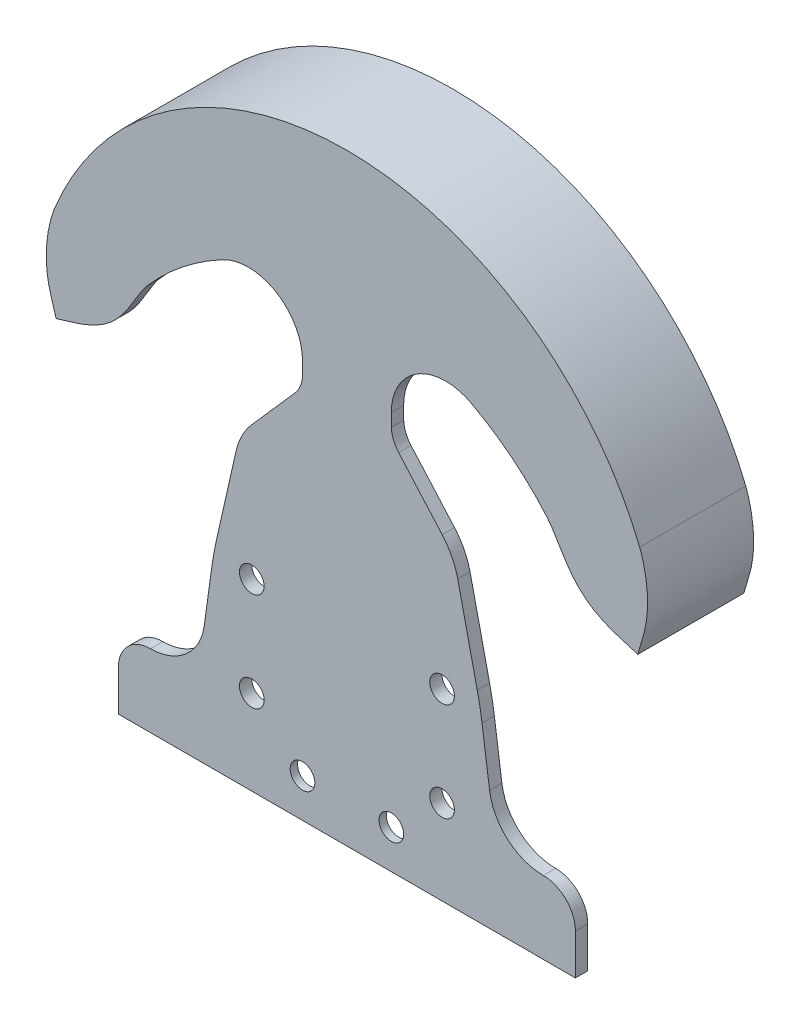
SolidWorks part; units mm, degrees
ref_plane "前视基准面" through (0, 0, 0) normal (0, 0, 1) x (1, 0, 0)
ref_plane "上视基准面" through (0, 0, 0) normal (0, 1, 0) x (1, 0, 0)
ref_plane "右视基准面" through (0, 0, 0) normal (1, 0, 0) x (0, 0, -1)
sketch "草图1" plane through (0, 0, 0) normal (0, 0, 1) x (1, 0, 0)
  line L50 (-253.4507, 153.8906) -> (-233.4507, 153.8906) construction
  line L51 (-253.4507, 153.8906) -> (-253.4507, 178.8906) construction
  line L52 (-233.4507, 153.8906) -> (-233.4507, 178.8906) construction
  line L56 (-261.4507, 145.8906) -> (-225.4507, 145.8906)
  line L57 (-225.4507, 145.8906) -> (-225.4507, 178.8906)
  line L58 (-261.4507, 145.8906) -> (-261.4507, 178.8906)
  arc A46 (-156.2727, 178.8906) -> (-189.3331, 205.3612) centre (-243.4507, 103.8906) ccw construction
  arc A47 (-297.5684, 205.3612) -> (-330.6287, 178.8906) centre (-243.4507, 103.8906) ccw construction
  arc A48 (-233.4507, 178.8906) -> (-189.3331, 205.3612) centre (-203.4507, 178.8906) cw construction
  arc A49 (-253.4507, 178.8906) -> (-297.5684, 205.3612) centre (-283.4507, 178.8906) ccw construction
  arc A50 (-354.6937, 178.8906) -> (-132.2077, 178.8906) centre (-243.4507, 133.8906) cw construction
  arc A56 (-225.4507, 178.8906) -> (-193.0978, 198.3024) centre (-203.4507, 178.8906) cw
  arc A57 (-162.3373, 173.6732) -> (-193.0978, 198.3024) centre (-243.4507, 103.8906) ccw
  arc A58 (-362.1099, 181.8906) -> (-124.7915, 181.8906) centre (-243.4507, 133.8906) cw
  arc A59 (-293.8037, 198.3024) -> (-324.5641, 173.6732) centre (-243.4507, 103.8906) ccw
  arc A60 (-261.4507, 178.8906) -> (-293.8037, 198.3024) centre (-283.4507, 178.8906) ccw
  spline S0 degree 3 poles (-330.6287, 178.8906) (-333.7557, 175.2558) (-339.6986, 163.334) (-346.9011, 156.6664) (-355.9507, 153.8906) knots 0 0 0 0 0.445001 1 1 1 1 construction
  spline S1 degree 3 poles (-156.2727, 178.8906) (-153.1457, 175.2558) (-147.2029, 163.334) (-140.0004, 156.6664) (-130.9507, 153.8906) knots 0 0 0 0 0.445001 1 1 1 1 construction
  spline S2 degree 3 poles (-354.6937, 178.8906) (-355.9795, 175.712) (-359.1189, 164.6336) (-355.9507, 153.8906) knots 0 0 0 0 1 1 1 1 construction
  spline S3 degree 3 poles (-132.2077, 178.8906) (-130.922, 175.712) (-127.7826, 164.6336) (-130.9507, 153.8906) knots 0 0 0 0 1 1 1 1 construction
  spline S12 degree 1 poles (-162.3373, 173.6732) (-125.565, 143.8707) knots 0 0 1 1 construction
  spline S13 degree 1 poles (-124.7915, 181.8906) (-125.565, 143.8707) knots 0 0 1 1 construction
  spline S14 degree 1 poles (-362.1099, 181.8906) (-361.3364, 143.8707) knots 0 0 1 1 construction
  spline S15 degree 1 poles (-324.5641, 173.6732) (-361.3364, 143.8707) knots 0 0 1 1 construction
  spline S16 degree 3 poles (-162.3373, 173.6732) (-162.1569, 173.4635) (-161.8222, 173.0548) (-161.0635, 172.0508) (-160.064, 170.5851) (-158.7871, 168.5438) (-156.9976, 165.5682) (-154.5713, 161.5499) (-151.6264, 157.5381) (-148.6726, 154.4947) (-146.127, 152.3645) (-143.2514, 150.4432) (-140.0504, 148.7514) (-137.1153, 147.5257) (-134.8798, 146.744) (-133.8248, 146.4053) (-133.3042, 146.2445) (-133.0182, 146.1569) (-132.4962, 145.9967) (-131.7617, 145.7715) (-130.5803, 145.4091) (-128.5158, 144.7759) (-126.7452, 144.2327) (-125.565, 143.8707) knots 0 0 0 0 0.036189 0.072379 0.144757 0.217136 0.289514 0.434271 0.579028 0.651407 0.723786 0.796164 0.868543 0.940921 0.97711 0.995205 0.999729 1.004252 1.0133 1.031394 1.049489 1.085678 1.158057 1.158057 1.158057 1.158057
  spline S17 degree 3 poles (-125.565, 143.8707) (-125.3193, 144.7038) (-124.9508, 145.9533) (-124.4595, 147.6195) (-124.091, 148.8688) (-123.7838, 149.9107) (-123.5384, 150.7425) (-123.3843, 151.2663) (-123.2626, 151.6764) (-123.1032, 152.2295) (-122.8609, 153.1288) (-122.4242, 154.9658) (-121.9752, 157.5299) (-121.6653, 160.535) (-121.5541, 163.4329) (-121.627, 167.132) (-122.0572, 171.3984) (-122.7563, 175.0715) (-123.3797, 177.5891) (-123.8587, 179.2553) (-124.2512, 180.4506) (-124.5608, 181.3048) (-124.7117, 181.6931) (-124.7915, 181.8906) knots 0 0 0 0 0.077543 0.116314 0.155085 0.193857 0.213242 0.232628 0.242321 0.252014 0.271399 0.310171 0.387713 0.465256 0.542799 0.620341 0.775427 0.930512 1.008055 1.085598 1.16314 1.201912 1.240683 1.240683 1.240683 1.240683
  spline S18 degree 3 poles (-362.1099, 181.8906) (-362.1898, 181.6931) (-362.3407, 181.3048) (-362.6502, 180.4506) (-363.0427, 179.2553) (-363.5217, 177.5891) (-364.1452, 175.0715) (-364.8442, 171.3984) (-365.2745, 167.132) (-365.3473, 163.4329) (-365.2362, 160.535) (-364.9262, 157.5299) (-364.4773, 154.9658) (-364.0406, 153.1288) (-363.7982, 152.2295) (-363.6389, 151.6764) (-363.5171, 151.2663) (-363.3631, 150.7425) (-363.1176, 149.9107) (-362.8104, 148.8688) (-362.442, 147.6195) (-361.9506, 145.9533) (-361.5821, 144.7038) (-361.3364, 143.8707) knots 0 0 0 0 0.038771 0.077543 0.155085 0.232628 0.310171 0.465256 0.620341 0.697884 0.775427 0.852969 0.930512 0.969283 0.988669 0.998362 1.008055 1.02744 1.046826 1.085598 1.124369 1.16314 1.240683 1.240683 1.240683 1.240683
  spline S19 degree 3 poles (-361.3364, 143.8707) (-360.1563, 144.2327) (-358.3856, 144.7759) (-356.3211, 145.4091) (-355.1397, 145.7715) (-354.4052, 145.9967) (-353.8832, 146.1569) (-353.5972, 146.2445) (-353.0767, 146.4053) (-352.0217, 146.744) (-349.7862, 147.5257) (-346.851, 148.7514) (-343.65, 150.4432) (-340.7744, 152.3645) (-338.2288, 154.4947) (-335.2751, 157.5381) (-332.3302, 161.5499) (-329.9038, 165.5682) (-328.1143, 168.5438) (-326.8375, 170.5851) (-325.838, 172.0508) (-325.0792, 173.0548) (-324.7446, 173.4635) (-324.5641, 173.6732) knots 0 0 0 0 0.072379 0.108568 0.126662 0.144757 0.153804 0.158328 0.162852 0.180946 0.217136 0.289514 0.361893 0.434271 0.50665 0.579028 0.723786 0.868543 0.940921 1.0133 1.085678 1.121868 1.158057 1.158057 1.158057 1.158057
  dimension "D2" = 8
extrude "凸台-拉伸6" add sketch "草图1" along normal blind 5
sketch "草图4" plane through (0, 0, 0) normal (0, 0, -1) x (-1, 0, 0)
  line L3 (261.4507, 145.8906) -> (261.4507, 178.8906)
  line L4 (225.4507, 178.8906) -> (225.4507, 145.8906)
  line L5 (225.4507, 145.8906) -> (261.4507, 145.8906)
  line L9 (125.565, 143.8707) -> (162.3373, 173.6732) construction
  line L10 (127.1703, 149.0333) -> (160.2404, 175.8353) construction
  line L11 (127.1703, 149.0333) -> (125.565, 143.8707)
  line L12 (359.7312, 149.0333) -> (361.3364, 143.8707)
  line L13 (324.5641, 173.6732) -> (361.3364, 143.8707) construction
  line L14 (225.4507, 178.8906) -> (225.4507, 145.8906) construction
  line L15 (228.4507, 178.8906) -> (228.4507, 148.8906) construction
  line L16 (225.4507, 145.8906) -> (261.4507, 145.8906) construction
  line L17 (228.4507, 148.8906) -> (258.4507, 148.8906) construction
  line L18 (261.4507, 145.8906) -> (261.4507, 178.8906) construction
  line L19 (258.4507, 148.8906) -> (258.4507, 178.8906) construction
  line L20 (326.6611, 175.8353) -> (359.7312, 149.0333) construction
  arc A2 (359.3288, 180.7656) -> (127.5726, 180.7656) centre (243.4507, 133.8906) ccw
  arc A5 (293.8037, 198.3024) -> (261.4507, 178.8906) centre (283.4507, 178.8906) ccw
  arc A6 (324.5641, 173.6732) -> (293.8037, 198.3024) centre (243.4507, 103.8906) ccw
  arc A7 (362.1099, 181.8906) -> (124.7915, 181.8906) centre (243.4507, 133.8906) ccw
  arc A8 (193.0978, 198.3024) -> (162.3373, 173.6732) centre (243.4507, 103.8906) ccw
  arc A9 (225.4507, 178.8906) -> (193.0978, 198.3024) centre (203.4507, 178.8906) ccw
  arc A12 (362.1099, 181.8906) -> (124.7915, 181.8906) centre (243.4507, 133.8906) ccw
  arc A15 (193.0978, 198.3024) -> (162.3373, 173.6732) centre (243.4507, 103.8906) ccw construction
  arc A16 (191.686, 200.9494) -> (160.2404, 175.8353) centre (243.4507, 103.8906) ccw construction
  arc A17 (228.4507, 178.8906) -> (191.686, 200.9494) centre (203.4507, 178.8906) ccw construction
  arc A18 (225.4507, 178.8906) -> (193.0978, 198.3024) centre (203.4507, 178.8906) ccw construction
  arc A19 (295.2154, 200.9494) -> (258.4507, 178.8906) centre (283.4507, 178.8906) ccw construction
  arc A20 (293.8037, 198.3024) -> (261.4507, 178.8906) centre (283.4507, 178.8906) ccw construction
  arc A21 (326.6611, 175.8353) -> (295.2154, 200.9494) centre (243.4507, 103.8906) ccw construction
  arc A22 (324.5641, 173.6732) -> (293.8037, 198.3024) centre (243.4507, 103.8906) ccw construction
  spline S1 degree 1 poles (359.7312, 149.0333) (359.3288, 180.7656) knots 0 0 1 1 construction
  spline S2 degree 1 poles (127.5726, 180.7656) (127.1703, 149.0333) knots 0 0 1 1 construction
  spline S4 degree 3 poles (-334.5281, 925.7249) (324.5328, 165.4388) (319.5248, 180.4044) (325.838, 172.0508) (326.8375, 170.5851) (328.1143, 168.5438) (329.9038, 165.5682) (332.3302, 161.5499) (335.2751, 157.5381) (338.2288, 154.4947) (340.7744, 152.3645) (343.65, 150.4432) (346.851, 148.7514) (349.7862, 147.5257) (352.0217, 146.744) (353.0767, 146.4053) (353.5972, 146.2445) (353.8832, 146.1569) (354.4052, 145.9967) (355.1397, 145.7715) (356.3211, 145.4091) (508.7612, 98.6521) (668.3407, 49.562) (-586.821, 461.6535) knots -1.059691 -1.059691 -1.059691 -1.059691 0.036189 0.072379 0.144757 0.217136 0.289514 0.434271 0.579028 0.651407 0.723786 0.796164 0.868543 0.940921 0.97711 0.995205 0.999729 1.004252 1.0133 1.031394 1.049489 1.085678 10.383805 10.383805 10.383805 10.383805 only from (324.5641, 173.6732) to (361.3364, 143.8707)
  spline S5 degree 3 poles (-250.6044, -2792.3967) (190.8544, -432.5756) (276.2458, -144.6702) (362.442, 147.6195) (362.8104, 148.8688) (363.1176, 149.9107) (363.3631, 150.7425) (363.5171, 151.2663) (363.6389, 151.6764) (363.7982, 152.2295) (364.0406, 153.1288) (364.4773, 154.9658) (364.9262, 157.5299) (365.2362, 160.535) (365.3473, 163.4329) (365.2745, 167.132) (364.8442, 171.3984) (364.1452, 175.0715) (363.5217, 177.5891) (363.0427, 179.2553) (362.6502, 180.4506) (357.7609, 193.9423) (356.6698, 170.7419) (-818.7559, 2939.1071) knots -27.051344 -27.051344 -27.051344 -27.051344 0.077543 0.116314 0.155085 0.193857 0.213242 0.232628 0.242321 0.252014 0.271399 0.310171 0.387713 0.465256 0.542799 0.620341 0.775427 0.930512 1.008055 1.085598 1.16314 1.201912 3.535098 3.535098 3.535098 3.535098 only from (361.3364, 143.8707) to (362.1099, 181.8906)
  spline S6 degree 3 poles (1305.6549, 2939.1014) (130.2317, 170.742) (129.1405, 193.9423) (124.2512, 180.4506) (123.8587, 179.2553) (123.3797, 177.5891) (122.7563, 175.0715) (122.0572, 171.3984) (121.627, 167.132) (121.5541, 163.4329) (121.6653, 160.535) (121.9752, 157.5299) (122.4242, 154.9658) (122.8609, 153.1288) (123.1032, 152.2295) (123.2626, 151.6764) (123.3843, 151.2663) (123.5384, 150.7425) (123.7838, 149.9107) (124.091, 148.8688) (124.4595, 147.6195) (210.6549, -144.6678) (296.0456, -432.5708) (737.4948, -2792.3377) knots -2.294413 -2.294413 -2.294413 -2.294413 0.038771 0.077543 0.155085 0.232628 0.310171 0.465256 0.620341 0.697884 0.775427 0.852969 0.930512 0.969283 0.988669 0.998362 1.008055 1.02744 1.046826 1.085598 1.124369 1.16314 28.291801 28.291801 28.291801 28.291801 only from (124.7915, 181.8906) to (125.565, 143.8707)
  spline S7 degree 3 poles (1073.7269, 461.6549) (-181.4396, 49.5619) (-21.8599, 98.652) (130.5803, 145.4091) (131.7617, 145.7715) (132.4962, 145.9967) (133.0182, 146.1569) (133.3042, 146.2445) (133.8248, 146.4053) (134.8798, 146.744) (137.1153, 147.5257) (140.0504, 148.7514) (143.2514, 150.4432) (146.127, 152.3645) (148.6726, 154.4947) (151.6264, 157.5381) (154.5713, 161.5499) (156.9976, 165.5682) (158.7871, 168.5438) (160.064, 170.5851) (161.0635, 172.0508) (167.3762, 180.4039) (162.3693, 165.4409) (821.2885, 925.5622) knots -9.225759 -9.225759 -9.225759 -9.225759 0.072379 0.108568 0.126662 0.144757 0.153804 0.158328 0.162852 0.180946 0.217136 0.289514 0.361893 0.434271 0.50665 0.579028 0.723786 0.868543 0.940921 1.0133 1.085678 1.121868 2.21767 2.21767 2.21767 2.21767 only from (125.565, 143.8707) to (162.3373, 173.6732)
  spline S9 degree 3 poles (361.3364, 143.8707) (361.5821, 144.7038) (361.9506, 145.9533) (362.442, 147.6195) (362.8104, 148.8688) (363.1176, 149.9107) (363.3631, 150.7425) (363.5171, 151.2663) (363.6389, 151.6764) (363.7982, 152.2295) (364.0406, 153.1288) (364.4773, 154.9658) (364.9262, 157.5299) (365.2362, 160.535) (365.3473, 163.4329) (365.2745, 167.132) (364.8442, 171.3984) (364.1452, 175.0715) (363.5217, 177.5891) (363.0427, 179.2553) (362.6502, 180.4506) (362.3407, 181.3048) (362.1898, 181.6931) (362.1099, 181.8906) knots 0 0 0 0 0.077543 0.116314 0.155085 0.193857 0.213242 0.232628 0.242321 0.252014 0.271399 0.310171 0.387713 0.465256 0.542799 0.620341 0.775427 0.930512 1.008055 1.085598 1.16314 1.201912 1.240683 1.240683 1.240683 1.240683
  spline S10 degree 3 poles (124.7915, 181.8906) (124.7117, 181.6931) (124.5608, 181.3048) (124.2512, 180.4506) (123.8587, 179.2553) (123.3797, 177.5891) (122.7563, 175.0715) (122.0572, 171.3984) (121.627, 167.132) (121.5541, 163.4329) (121.6653, 160.535) (121.9752, 157.5299) (122.4242, 154.9658) (122.8609, 153.1288) (123.1032, 152.2295) (123.2626, 151.6764) (123.3843, 151.2663) (123.5384, 150.7425) (123.7838, 149.9107) (124.091, 148.8688) (124.4595, 147.6195) (124.9508, 145.9533) (125.3193, 144.7038) (125.565, 143.8707) knots 0 0 0 0 0.038771 0.077543 0.155085 0.232628 0.310171 0.465256 0.620341 0.697884 0.775427 0.852969 0.930512 0.969283 0.988669 0.998362 1.008055 1.02744 1.046826 1.085598 1.124369 1.16314 1.240683 1.240683 1.240683 1.240683
  spline S13 degree 3 poles (359.7312, 149.0333) (359.9503, 149.7764) (360.224, 150.703) (360.5533, 151.822) (360.6885, 152.2782) (360.8038, 152.6713) (360.9349, 153.1325) (361.1289, 153.859) (361.3909, 154.9529) (361.7356, 156.6602) (362.0512, 158.7728) (362.2681, 161.2567) (362.3663, 164.4692) (362.1847, 168.2714) (361.6304, 172.3741) (361.0068, 175.3191) (360.4768, 177.3386) (360.0784, 178.6753) (359.7576, 179.6311) (359.5087, 180.3104) (359.3912, 180.6114) (359.3288, 180.7656) knots 0.133855 0.133855 0.133855 0.133855 0.203031 0.220326 0.23762 0.246267 0.254914 0.272208 0.306797 0.341385 0.410562 0.479739 0.548915 0.687269 0.825622 0.963976 1.033153 1.102329 1.171506 1.206094 1.240683 1.240683 1.240683 1.240683
  spline S14 degree 3 poles (127.5726, 180.7656) (127.5102, 180.6114) (127.3927, 180.3104) (127.1438, 179.6311) (126.8231, 178.6753) (126.4247, 177.3386) (125.8946, 175.3191) (125.2711, 172.3741) (124.7168, 168.2714) (124.5352, 164.4692) (124.6334, 161.2567) (124.8502, 158.7728) (125.1658, 156.6602) (125.5105, 154.9529) (125.7726, 153.859) (125.9665, 153.1325) (126.0976, 152.6713) (126.2129, 152.2782) (126.3481, 151.822) (126.6775, 150.703) (126.9511, 149.7764) (127.1703, 149.0333) knots 0 0 0 0 0.034588 0.069177 0.138354 0.20753 0.276707 0.415061 0.553414 0.691768 0.760944 0.830121 0.899298 0.933886 0.968475 0.985769 0.994416 1.003063 1.020357 1.037651 1.106828 1.106828 1.106828 1.106828
  dimension "D1" = 0
  dimension "D2" = 3
extrude "凸台-拉伸7" add sketch "草图4" along normal blind 35
sketch "草图5" plane through (0, 0, -35) normal (0, 0, -1) x (-1, 0, 0)
  line L0 (243.4507, 145.8906) -> (243.4507, 269.2971) construction
  line L2 (125.565, 143.8707) -> (127.1703, 149.0333)
  line L3 (359.7312, 149.0333) -> (361.3364, 143.8707)
  line L5 (124.7915, 181.8906) -> (125.565, 143.8707) construction
  line L6 (154.9193, 175.9166) -> (155.5588, 144.4809) construction
  line L7 (361.3364, 143.8707) -> (362.1099, 181.8906) construction
  line L8 (331.3427, 144.4809) -> (331.9822, 175.9166) construction
  arc A0 (331.9822, 175.9166) -> (154.9193, 175.9166) centre (243.4507, 133.8906) ccw
  arc A2 (362.1099, 181.8906) -> (124.7915, 181.8906) centre (243.4507, 133.8906) ccw
  arc A3 (359.3288, 180.7656) -> (127.5726, 180.7656) centre (243.4507, 133.8906) ccw
  arc A4 (362.1099, 181.8906) -> (124.7915, 181.8906) centre (243.4507, 133.8906) ccw
  spline S1 degree 3 poles (361.3364, 143.8707) (346.8534, 150.3802) (338.6969, 161.7715) (331.9822, 175.9166) knots 0 0 0 0 1 1 1 1
  spline S4 degree 3 poles (-250.604, -2792.3952) (190.8545, -432.5755) (276.2458, -144.6702) (362.442, 147.6195) (362.8104, 148.8688) (363.1176, 149.9107) (363.3631, 150.7425) (363.5171, 151.2663) (363.6389, 151.6764) (363.7982, 152.2295) (364.0406, 153.1288) (364.4773, 154.9658) (364.9262, 157.5299) (365.2362, 160.535) (365.3473, 163.4329) (365.2744, 167.132) (364.8442, 171.3985) (364.1452, 175.0715) (363.5217, 177.5891) (363.0427, 179.2553) (362.6502, 180.4506) (357.7609, 193.9423) (356.67, 170.7415) (-818.7021, 2938.9834) knots -27.063744 -27.063744 -27.063744 -27.063744 0.065136 0.103907 0.142679 0.18145 0.200836 0.220221 0.229914 0.239607 0.258993 0.297764 0.375307 0.452849 0.530392 0.607935 0.76302 0.918105 0.995648 1.073191 1.150733 1.189505 3.522691 3.522691 3.522691 3.522691 only from (361.3364, 143.8707) to (362.1099, 181.8906)
  spline S5 degree 3 poles (1305.6549, 2939.1014) (130.2317, 170.742) (129.1405, 193.9423) (124.2512, 180.4506) (123.8587, 179.2553) (123.3797, 177.5891) (122.7563, 175.0715) (122.0572, 171.3984) (121.627, 167.132) (121.5541, 163.4329) (121.6653, 160.535) (121.9752, 157.5299) (122.4242, 154.9658) (122.8609, 153.1288) (123.1032, 152.2295) (123.2626, 151.6764) (123.3843, 151.2663) (123.5384, 150.7425) (123.7838, 149.9107) (124.091, 148.8688) (124.4595, 147.6195) (210.6549, -144.6678) (296.0456, -432.5708) (737.4948, -2792.3377) knots -2.294413 -2.294413 -2.294413 -2.294413 0.038771 0.077543 0.155085 0.232628 0.310171 0.465256 0.620341 0.697884 0.775427 0.852969 0.930512 0.969283 0.988669 0.998362 1.008055 1.02744 1.046826 1.085598 1.124369 1.16314 28.291801 28.291801 28.291801 28.291801 only from (124.7915, 181.8906) to (125.565, 143.8707)
  spline S6 degree 3 poles (280.6603, -839.1112) (148.6074, 82.2121) (138.2801, 111.2793) (126.3481, 151.822) (126.2129, 152.2782) (126.0976, 152.6713) (125.9665, 153.1325) (125.7726, 153.859) (125.5105, 154.9529) (125.1658, 156.6602) (124.8502, 158.7728) (124.6334, 161.2567) (124.5352, 164.4692) (124.7168, 168.2714) (125.2711, 172.3741) (125.8946, 175.3191) (126.4247, 177.3386) (126.8231, 178.6753) (127.1438, 179.6311) (129.9096, 187.1786) (129.4062, 176.9576) (509.2581, 1104.9895) knots -3.655588 -3.655588 -3.655588 -3.655588 0.069177 0.086471 0.103765 0.112412 0.121059 0.138354 0.172942 0.20753 0.276707 0.345884 0.415061 0.553414 0.691768 0.830121 0.899298 0.968475 1.037651 1.07224 2.505599 2.505599 2.505599 2.505599 only from (127.1703, 149.0333) to (127.5726, 180.7656)
  spline S7 degree 3 poles (-22.3799, 1105.0463) (357.4953, 176.9572) (356.9918, 187.1788) (359.7576, 179.6311) (360.0784, 178.6753) (360.4768, 177.3386) (361.0068, 175.3191) (361.6304, 172.3741) (362.1847, 168.2714) (362.3663, 164.4692) (362.2681, 161.2567) (362.0512, 158.7728) (361.7356, 156.6602) (361.3909, 154.9529) (361.1289, 153.859) (360.9349, 153.1325) (360.8038, 152.6713) (360.6885, 152.2782) (360.5533, 151.822) (348.6213, 111.2793) (338.2941, 82.2121) (206.2413, -839.1099) knots -1.264946 -1.264946 -1.264946 -1.264946 0.168443 0.203031 0.272208 0.341385 0.410562 0.548915 0.687269 0.825622 0.894799 0.963976 1.033153 1.067741 1.102329 1.119624 1.128271 1.136918 1.154212 1.171506 4.896269 4.896269 4.896269 4.896269 only from (359.3288, 180.7656) to (359.7312, 149.0333)
  spline S8 degree 3 poles (361.3364, 143.8707) (361.5821, 144.7038) (361.9506, 145.9533) (362.442, 147.6195) (362.8104, 148.8688) (363.1176, 149.9107) (363.3631, 150.7425) (363.5171, 151.2663) (363.6389, 151.6764) (363.7982, 152.2295) (364.0406, 153.1288) (364.4773, 154.9658) (364.9262, 157.5299) (365.2362, 160.535) (365.3473, 163.4329) (365.2744, 167.132) (364.8442, 171.3985) (364.1452, 175.0715) (363.5217, 177.5891) (363.0427, 179.2553) (362.6502, 180.4506) (362.3407, 181.3048) (362.1898, 181.6931) (362.1099, 181.8906) knots -0.012407 -0.012407 -0.012407 -0.012407 0.065136 0.103907 0.142679 0.18145 0.200836 0.220221 0.229914 0.239607 0.258993 0.297764 0.375307 0.452849 0.530392 0.607935 0.76302 0.918105 0.995648 1.073191 1.150733 1.189505 1.228276 1.228276 1.228276 1.228276
  spline S9 degree 3 poles (124.7915, 181.8906) (124.7117, 181.6931) (124.5608, 181.3048) (124.2512, 180.4506) (123.8587, 179.2553) (123.3797, 177.5891) (122.7563, 175.0715) (122.0572, 171.3984) (121.627, 167.132) (121.5541, 163.4329) (121.6653, 160.535) (121.9752, 157.5299) (122.4242, 154.9658) (122.8609, 153.1288) (123.1032, 152.2295) (123.2626, 151.6764) (123.3843, 151.2663) (123.5384, 150.7425) (123.7838, 149.9107) (124.091, 148.8688) (124.4595, 147.6195) (124.9508, 145.9533) (125.3193, 144.7038) (125.565, 143.8707) knots 0 0 0 0 0.038771 0.077543 0.155085 0.232628 0.310171 0.465256 0.620341 0.697884 0.775427 0.852969 0.930512 0.969283 0.988669 0.998362 1.008055 1.02744 1.046826 1.085598 1.124369 1.16314 1.240683 1.240683 1.240683 1.240683
  spline S10 degree 3 poles (125.565, 143.8707) (140.048, 150.3802) (148.2046, 161.7715) (154.9193, 175.9166) knots 0 0 0 0 1 1 1 1
  dimension "D1" = 0
extrude "凸台-拉伸9" add sketch "草图5" along normal blind 3
sketch "草图7" plane through (0, 0, 5) normal (0, 0, 1) x (1, 0, 0)
  line L3 (-261.4507, 178.8906) -> (-261.4507, 145.8906)
  line L4 (-261.4507, 145.8906) -> (-225.4507, 145.8906)
  line L5 (-225.4507, 145.8906) -> (-225.4507, 178.8906)
  line L8 (-225.4507, 173.6266) -> (-225.4507, 178.8906)
  line L35 (-301.286, 66.1064) -> (-298.218, 88.2296)
  line L36 (-296.2945, 98.8105) -> (-288.3797, 133.9009)
  line L37 (-282.0717, 146.2538) -> (-264.4482, 166.2496)
  line L38 (-261.4507, 174.1841) -> (-261.4507, 178.8906)
  line L41 (-204.8427, 146.2538) -> (-222.4662, 166.2496)
  line L42 (-190.6199, 98.8105) -> (-198.5347, 133.9009)
  line L43 (-185.6284, 66.1064) -> (-188.6964, 88.2296)
  line L54 (-336.0774, 34.1284) -> (-336.0774, 17.6479)
  line L55 (-336.0774, 17.6479) -> (-150.8369, 17.6479)
  line L56 (-150.8369, 34.1284) -> (-150.8369, 17.6479)
  arc A5 (-193.0978, 198.3024) -> (-225.4507, 178.8906) centre (-203.4507, 178.8906) ccw
  arc A6 (-162.3373, 173.6732) -> (-193.0978, 198.3024) centre (-243.4507, 103.8906) ccw
  arc A7 (-124.7915, 181.8906) -> (-362.1099, 181.8906) centre (-243.4507, 133.8906) ccw
  arc A8 (-293.8037, 198.3024) -> (-324.5641, 173.6732) centre (-243.4507, 103.8906) ccw
  arc A9 (-261.4507, 178.8906) -> (-293.8037, 198.3024) centre (-283.4507, 178.8906) ccw
  arc A10 (-193.0978, 198.3024) -> (-225.4507, 178.8906) centre (-203.4507, 178.8906) ccw
  arc A11 (-162.3373, 173.6732) -> (-193.0978, 198.3024) centre (-243.4507, 103.8906) ccw
  arc A12 (-124.7915, 181.8906) -> (-362.1099, 181.8906) centre (-243.4507, 133.8906) ccw
  arc A13 (-293.8037, 198.3024) -> (-324.5641, 173.6732) centre (-243.4507, 103.8906) ccw
  arc A14 (-261.4507, 178.8906) -> (-293.8037, 198.3024) centre (-283.4507, 178.8906) ccw
  arc A36 (-323.0774, 47.1284) -> (-301.286, 66.1064) centre (-323.0774, 69.1284) ccw
  arc A37 (-298.218, 88.2296) -> (-296.2945, 98.8105) centre (-171.4313, 70.6469) cw
  arc A38 (-288.3797, 133.9009) -> (-282.0717, 146.2538) centre (-261.0658, 127.7402) cw
  arc A39 (-264.4482, 166.2496) -> (-261.4507, 174.1841) centre (-273.4507, 174.1841) ccw
  arc A40 (-222.4662, 166.2496) -> (-225.4507, 173.6266) centre (-213.4637, 174.1841) cw
  arc A41 (-204.8427, 146.2538) -> (-198.5347, 133.9009) centre (-225.8485, 127.7402) cw
  arc A42 (-188.6964, 88.2296) -> (-190.6199, 98.8105) centre (-315.4831, 70.6469) ccw
  arc A43 (-163.8369, 47.1284) -> (-185.6284, 66.1064) centre (-163.8369, 69.1284) cw
  arc A45 (-336.0774, 34.1284) -> (-323.0774, 47.1284) centre (-323.0774, 34.1284) cw
  arc A46 (-150.8369, 34.1284) -> (-163.8369, 47.1284) centre (-163.8369, 34.1284) ccw
  spline S4 degree 3 poles (-3430.7462, 3955.4122) (-150.4817, 134.4946) (-171.4156, 185.7488) (-161.0635, 172.0508) (-160.064, 170.5851) (-158.7871, 168.5438) (-156.9976, 165.5682) (-154.5713, 161.5499) (-151.6264, 157.5381) (-148.6726, 154.4947) (-146.127, 152.3645) (-143.2514, 150.4432) (-140.0504, 148.7514) (-137.1153, 147.5257) (-134.8798, 146.744) (-133.8248, 146.4053) (-133.3042, 146.2445) (-133.0182, 146.1569) (-132.4962, 145.9967) (-131.7617, 145.7715) (-130.5803, 145.4091) (108.4504, 72.0927) (365.4909, -7.1004) (-4875.1127, 1705.8776) knots -1.830248 -1.830248 -1.830248 -1.830248 0.036189 0.072379 0.144757 0.217136 0.289514 0.434271 0.579028 0.651407 0.723786 0.796164 0.868543 0.940921 0.97711 0.995205 0.999729 1.004252 1.0133 1.031394 1.049489 1.085678 15.696264 15.696264 15.696264 15.696264 only from (-162.3373, 173.6732) to (-125.565, 143.8707)
  spline S5 degree 3 poles (-1100.1242, -4759.1447) (-334.975, -563.7382) (-230.293, -211.26) (-124.4595, 147.6195) (-124.091, 148.8688) (-123.7838, 149.9107) (-123.5384, 150.7425) (-123.3843, 151.2663) (-123.2626, 151.6764) (-123.1032, 152.2295) (-122.8609, 153.1288) (-122.4242, 154.9658) (-121.9752, 157.5299) (-121.6653, 160.535) (-121.5541, 163.4329) (-121.627, 167.132) (-122.0572, 171.3984) (-122.7563, 175.0715) (-123.3797, 177.5891) (-123.8587, 179.2553) (-124.2512, 180.4506) (-130.0019, 196.3193) (-130.5081, 161.0995) (-2085.8561, 4779.5647) knots -33.249546 -33.249546 -33.249546 -33.249546 0.077543 0.116314 0.155085 0.193857 0.213242 0.232628 0.242321 0.252014 0.271399 0.310171 0.387713 0.465256 0.542799 0.620341 0.775427 0.930512 1.008055 1.085598 1.16314 1.201912 3.966644 3.966644 3.966644 3.966644 only from (-125.565, 143.8707) to (-124.7915, 181.8906)
  spline S6 degree 3 poles (1599.0286, 4779.7392) (-356.3933, 161.0986) (-356.8995, 196.3195) (-362.6502, 180.4506) (-363.0427, 179.2553) (-363.5217, 177.5891) (-364.1452, 175.0715) (-364.8442, 171.3984) (-365.2745, 167.132) (-365.3473, 163.4329) (-365.2362, 160.535) (-364.9262, 157.5299) (-364.4773, 154.9658) (-364.0406, 153.1288) (-363.7982, 152.2295) (-363.6389, 151.6764) (-363.5171, 151.2663) (-363.3631, 150.7425) (-363.1176, 149.9107) (-362.8104, 148.8688) (-362.442, 147.6195) (-256.6083, -211.2605) (-151.9262, -563.7392) (613.226, -4759.163) knots -2.725996 -2.725996 -2.725996 -2.725996 0.038771 0.077543 0.155085 0.232628 0.310171 0.465256 0.620341 0.697884 0.775427 0.852969 0.930512 0.969283 0.988669 0.998362 1.008055 1.02744 1.046826 1.085598 1.124369 1.16314 34.490277 34.490277 34.490277 34.490277 only from (-362.1099, 181.8906) to (-361.3364, 143.8707)
  spline S7 degree 3 poles (4388.2756, 1705.8986) (-852.3944, -7.1011) (-595.3528, 72.0924) (-356.3211, 145.4091) (-355.1397, 145.7715) (-354.4052, 145.9967) (-353.8832, 146.1569) (-353.5972, 146.2445) (-353.0767, 146.4053) (-352.0217, 146.744) (-349.7862, 147.5257) (-346.851, 148.7514) (-343.65, 150.4432) (-340.7744, 152.3645) (-338.2288, 154.4947) (-335.2751, 157.5381) (-332.3302, 161.5499) (-329.9038, 165.5682) (-328.1143, 168.5438) (-326.8375, 170.5851) (-325.838, 172.0508) (-315.4854, 185.7494) (-336.4219, 134.4893) (2944.3615, 3956.0141) knots -14.538267 -14.538267 -14.538267 -14.538267 0.072379 0.108568 0.126662 0.144757 0.153804 0.158328 0.162852 0.180946 0.217136 0.289514 0.361893 0.434271 0.50665 0.579028 0.723786 0.868543 0.940921 1.0133 1.085678 1.121868 2.988403 2.988403 2.988403 2.988403 only from (-361.3364, 143.8707) to (-324.5641, 173.6732)
  spline S8 degree 3 poles (-162.3373, 173.6732) (-162.1569, 173.4635) (-161.8222, 173.0548) (-161.0635, 172.0508) (-160.064, 170.5851) (-158.7871, 168.5438) (-156.9976, 165.5682) (-154.5713, 161.5499) (-151.6264, 157.5381) (-148.6726, 154.4947) (-146.127, 152.3645) (-143.2514, 150.4432) (-140.0504, 148.7514) (-137.1153, 147.5257) (-134.8798, 146.744) (-133.8248, 146.4053) (-133.3042, 146.2445) (-133.0182, 146.1569) (-132.4962, 145.9967) (-131.7617, 145.7715) (-130.5803, 145.4091) (-128.5158, 144.7759) (-126.7452, 144.2327) (-125.565, 143.8707) knots 0 0 0 0 0.036189 0.072379 0.144757 0.217136 0.289514 0.434271 0.579028 0.651407 0.723786 0.796164 0.868543 0.940921 0.97711 0.995205 0.999729 1.004252 1.0133 1.031394 1.049489 1.085678 1.158057 1.158057 1.158057 1.158057
  spline S9 degree 3 poles (-125.565, 143.8707) (-125.3193, 144.7038) (-124.9508, 145.9533) (-124.4595, 147.6195) (-124.091, 148.8688) (-123.7838, 149.9107) (-123.5384, 150.7425) (-123.3843, 151.2663) (-123.2626, 151.6764) (-123.1032, 152.2295) (-122.8609, 153.1288) (-122.4242, 154.9658) (-121.9752, 157.5299) (-121.6653, 160.535) (-121.5541, 163.4329) (-121.627, 167.132) (-122.0572, 171.3984) (-122.7563, 175.0715) (-123.3797, 177.5891) (-123.8587, 179.2553) (-124.2512, 180.4506) (-124.5608, 181.3048) (-124.7117, 181.6931) (-124.7915, 181.8906) knots 0 0 0 0 0.077543 0.116314 0.155085 0.193857 0.213242 0.232628 0.242321 0.252014 0.271399 0.310171 0.387713 0.465256 0.542799 0.620341 0.775427 0.930512 1.008055 1.085598 1.16314 1.201912 1.240683 1.240683 1.240683 1.240683
  spline S10 degree 3 poles (-362.1099, 181.8906) (-362.1898, 181.6931) (-362.3407, 181.3048) (-362.6502, 180.4506) (-363.0427, 179.2553) (-363.5217, 177.5891) (-364.1452, 175.0715) (-364.8442, 171.3984) (-365.2745, 167.132) (-365.3473, 163.4329) (-365.2362, 160.535) (-364.9262, 157.5299) (-364.4773, 154.9658) (-364.0406, 153.1288) (-363.7982, 152.2295) (-363.6389, 151.6764) (-363.5171, 151.2663) (-363.3631, 150.7425) (-363.1176, 149.9107) (-362.8104, 148.8688) (-362.442, 147.6195) (-361.9506, 145.9533) (-361.5821, 144.7038) (-361.3364, 143.8707) knots 0 0 0 0 0.038771 0.077543 0.155085 0.232628 0.310171 0.465256 0.620341 0.697884 0.775427 0.852969 0.930512 0.969283 0.988669 0.998362 1.008055 1.02744 1.046826 1.085598 1.124369 1.16314 1.240683 1.240683 1.240683 1.240683
  spline S11 degree 3 poles (-361.3364, 143.8707) (-360.1563, 144.2327) (-358.3856, 144.7759) (-356.3211, 145.4091) (-355.1397, 145.7715) (-354.4052, 145.9967) (-353.8832, 146.1569) (-353.5972, 146.2445) (-353.0767, 146.4053) (-352.0217, 146.744) (-349.7862, 147.5257) (-346.851, 148.7514) (-343.65, 150.4432) (-340.7744, 152.3645) (-338.2288, 154.4947) (-335.2751, 157.5381) (-332.3302, 161.5499) (-329.9038, 165.5682) (-328.1143, 168.5438) (-326.8375, 170.5851) (-325.838, 172.0508) (-325.0792, 173.0548) (-324.7446, 173.4635) (-324.5641, 173.6732) knots 0 0 0 0 0.072379 0.108568 0.126662 0.144757 0.153804 0.158328 0.162852 0.180946 0.217136 0.289514 0.361893 0.434271 0.50665 0.579028 0.723786 0.868543 0.940921 1.0133 1.085678 1.121868 1.158057 1.158057 1.158057 1.158057
  point P17 (0, 0)
  dimension "D1" = 0
extrude "凸台-拉伸10" add sketch "草图7" against normal blind 5
sketch "草图10" plane through (0, 0, 0) normal (0, 0, -1) x (-1, 0, 0)
  line L0 (336.0774, 17.6479) -> (150.8369, 17.6479) construction
  line L1 (213.4572, 77.6479) -> (273.4572, 77.6479)
  line L2 (213.4572, 77.6479) -> (213.4572, 17.6479)
  line L3 (213.4572, 17.6479) -> (273.4572, 17.6479)
  line L4 (273.4572, 77.6479) -> (273.4572, 17.6479)
  line L5 (243.4572, 17.6479) -> (243.4572, 124.7334) construction
  line L6 (150.8369, 17.6479) -> (150.8369, 34.1284) construction
  line L7 (336.0774, 34.1284) -> (336.0774, 17.6479) construction
  dimension "D1" = 60
  dimension "D2" = 60
extrude "切除-拉伸1" cut sketch "草图10" against normal blind 2
sketch "草图11" plane through (0, 0, 0) normal (0, 0, -1) x (-1, 0, 0)
  line L0 (243.4572, 17.6479) -> (243.4572, 104.9396) construction
  line L2 (150.8369, 17.6479) -> (150.8369, 34.1284) construction
  line L3 (336.0774, 34.1284) -> (336.0774, 17.6479) construction
  circle A0 centre (204.8922, 92.0501) radius 5
  circle A1 centre (204.8922, 52.0501) radius 5
  circle A2 centre (282.0222, 52.0501) radius 5
  circle A3 centre (282.0222, 92.0501) radius 5
  point P14 (208.6452, 128.0241)
  point P15 (203.1675, 88.1153)
  point P16 (204.8922, 92.0501)
  dimension "D1" = 10
  dimension "D2" = 10
  dimension "D3" = 40
extrude "切除-拉伸2" cut sketch "草图11" against normal through all
sketch "草图12" plane through (0, 0, 2) normal (0, 0, -1) x (-1, 0, 0)
  line L3 (243.4572, 77.6479) -> (243.4572, 65.1577) construction
  line L4 (213.4572, 77.6479) -> (213.4572, 17.6479) construction
  line L5 (273.4572, 77.6479) -> (213.4572, 77.6479) construction
  line L6 (273.4572, 17.6479) -> (273.4572, 77.6479) construction
  circle A0 centre (225.4572, 65.6479) radius 5
  circle A1 centre (261.4572, 65.6479) radius 5
  dimension "D1" = 10
  dimension "D2" = 12
  dimension "D3" = 12
extrude "凸台-拉伸11" add sketch "草图12" along normal blind 8.5
sketch "草图13" plane through (0, 0, 2) normal (0, 0, -1) x (-1, 0, 0)
  line L0 (213.4572, 47.6479) -> (239.3547, 47.6479) construction
  line L2 (273.4572, 77.6479) -> (213.4572, 77.6479) construction
  line L3 (213.4572, 17.6479) -> (273.4572, 17.6479) construction
  line L4 (243.4572, 77.6479) -> (243.4572, 0) construction
  line L5 (213.4572, 77.6479) -> (213.4572, 17.6479) construction
  line L6 (273.4572, 17.6479) -> (273.4572, 77.6479) construction
  circle A0 centre (225.4572, 33.283) radius 5
  circle A1 centre (261.4572, 65.6479) radius 5 construction
  circle A2 centre (225.4572, 65.6479) radius 5 construction
  circle A3 centre (261.4572, 65.6479) radius 5 construction
  circle A4 centre (225.4572, 65.6479) radius 5 construction
  circle A5 centre (261.4572, 33.283) radius 5
extrude "切除-拉伸3" cut sketch "草图13" against normal through all
